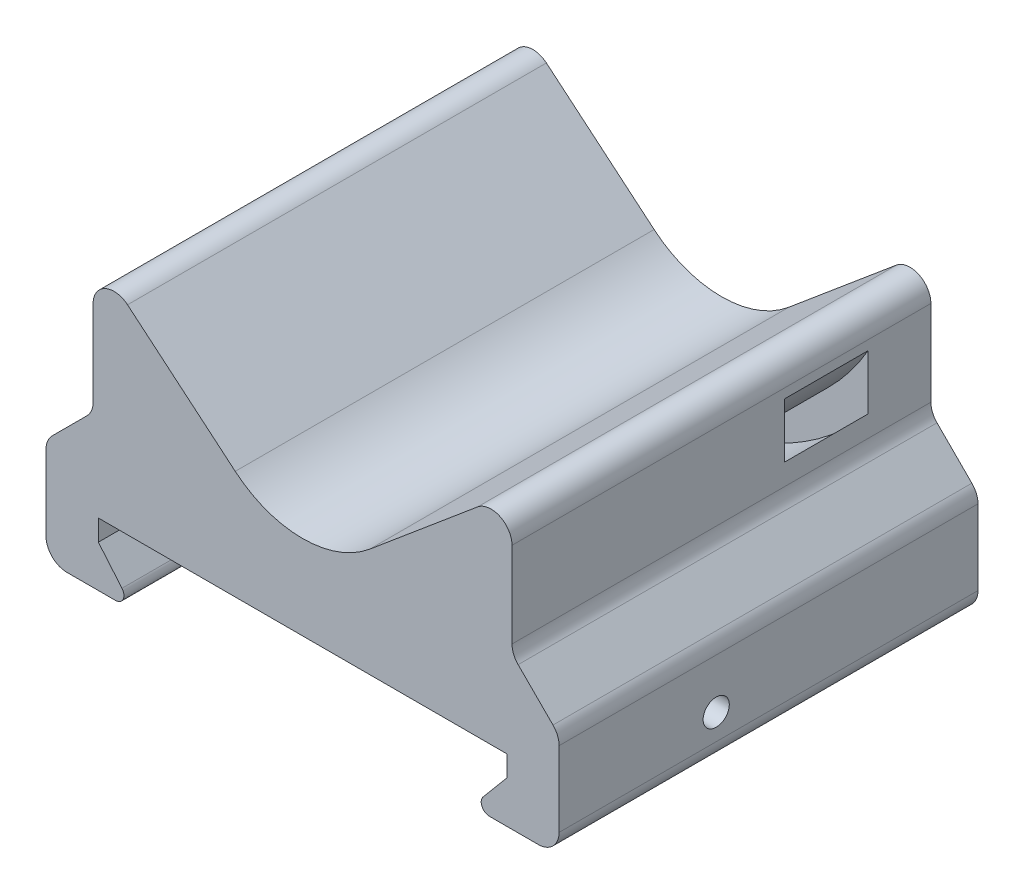
SolidWorks part; units mm, degrees
ref_plane "Front Plane" through (0, 0, 0) normal (0, 0, 1) x (1, 0, 0)
ref_plane "Top Plane" through (0, 0, 0) normal (0, 1, 0) x (1, 0, 0)
ref_plane "Right Plane" through (0, 0, 0) normal (1, 0, 0) x (0, 0, -1)
sketch "Sketch1" plane through (0, 0, 0) normal (0, 0, 1) x (1, 0, 0)
  line L0 (0, 15.6125) -> (0, -8.5333) construction
  line L1 (6.4279, 10.3936) -> (16.7144, 19.0251)
  line L2 (20, 17.493) -> (20, 9.3284)
  line L3 (20.5858, 7.9142) -> (23.9142, 4.5858)
  line L4 (24.5, 3.1716) -> (24.5, -4)
  line L5 (22.5, -6) -> (17.8592, -6)
  line L7 (19.5, 0) -> (-19.5, 0)
  line L9 (-22.5, -6) -> (-17.8592, -6)
  line L10 (-24.5, 3.1716) -> (-24.5, -4)
  line L11 (-20.5858, 7.9142) -> (-23.9142, 4.5858)
  line L12 (-20, 17.493) -> (-20, 9.3284)
  line L13 (-6.4279, 10.3936) -> (-16.7144, 19.0251)
  line L14 (-19.05, -0.1) -> (19.05, -0.1) construction
  line L15 (19.05, -0.1) -> (19.05, -2.1) construction
  line L16 (19.05, -2.1) -> (13.05, -8.1) construction
  line L17 (13.05, -8.1) -> (-13.05, -8.1) construction
  line L18 (-13.05, -8.1) -> (-19.05, -2.1) construction
  line L19 (-19.05, -0.1) -> (-19.05, -2.1) construction
  line L20 (17.2464, -4.6858) -> (19.5, -2)
  line L21 (19.5, -2) -> (19.5, 0)
  line L22 (-19.5, -2) -> (-19.5, 0)
  line L23 (-17.2464, -4.6858) -> (-19.5, -2)
  arc A0 (-6.4279, 10.3936) -> (6.4279, 10.3936) centre (0, 18.0541) ccw
  arc A1 (20, 9.3284) -> (20.5858, 7.9142) centre (22, 9.3284) ccw
  arc A2 (23.9142, 4.5858) -> (24.5, 3.1716) centre (22.5, 3.1716) cw
  arc A3 (24.5, -4) -> (22.5, -6) centre (22.5, -4) cw
  arc A4 (-22.5, -6) -> (-24.5, -4) centre (-22.5, -4) cw
  arc A5 (-24.5, 3.1716) -> (-23.9142, 4.5858) centre (-22.5, 3.1716) cw
  arc A6 (-20.5858, 7.9142) -> (-20, 9.3284) centre (-22, 9.3284) ccw
  arc A7 (16.7144, 19.0251) -> (20, 17.493) centre (18, 17.493) cw
  arc A8 (-20, 17.493) -> (-16.7144, 19.0251) centre (-18, 17.493) cw
  arc A9 (17.8592, -6) -> (17.2464, -4.6858) centre (17.8592, -5.2) cw
  arc A10 (-17.2464, -4.6858) -> (-17.8592, -6) centre (-17.8592, -5.2) cw
  point P11 (0, 0)
  point P19 (0, 5)
  point P22 (20, 8.5)
  point P25 (24.5, 4)
  point P28 (24.5, -6)
  point P31 (-24.5, -6)
  point P34 (-24.5, 4)
  point P37 (-20, 8.5)
  point P40 (20, 21.782)
  point P43 (-20, 21.782)
  point P51 (0, -8.1)
  point P52 (0, -0.1)
  point P56 (16.1436, -6)
  point P59 (-16.1436, -6)
  dimension "D10" = 10
  dimension "D11" = 2
  dimension "D18" = 0.8
  dimension "D1" = 19.5
  dimension "D2" = 5
  dimension "D3" = 20
  dimension "D4" = 135
  dimension "D5" = 50
  dimension "D6" = 6
  dimension "D7" = 4
  dimension "D8" = 50
  dimension "D9" = 5
  dimension "D12" = 38.1
  dimension "D13" = 135
  dimension "D14" = 8
  dimension "D15" = 2
  dimension "D16" = 0.2
  dimension "D17" = 2
extrude "Boss-Extrude1" add sketch "Sketch1" along normal blind 40
sketch "Sketch2" plane through (0, 0, 0) normal (1, 0, 0) x (0, 0, -1)
  line L0 (-40, 0) -> (0, 0) construction
  line L1 (-6, 5) -> (-14, 5)
  line L2 (-6, 5) -> (-6, 2)
  line L3 (-6, 2) -> (-14, 2)
  line L4 (-14, 5) -> (-14, 2)
  line L5 (0, 4.5858) -> (0, 7.9142) construction
  line L6 (-46, 5) -> (-54, 5)
  line L7 (-46, 5) -> (-46, 2)
  line L8 (-46, 2) -> (-54, 2)
  line L9 (-54, 5) -> (-54, 2)
  line L10 (-86, 5) -> (-94, 5)
  line L11 (-86, 5) -> (-86, 2)
  line L12 (-86, 2) -> (-94, 2)
  line L13 (-94, 5) -> (-94, 2)
  line L14 (-29.3538, 28.0541) -> (55.5998, 28.0541) construction
  line L15 (-40, 8.0541) -> (0, 8.0541) construction
  dimension "D1" = 8
  dimension "D2" = 3
  dimension "D3" = 2
  dimension "D4" = 6
  dimension "D6" = 20
  dimension "D5" = 3
revolve "Cut-Revolve1" cut sketch "Sketch2" angle 360 about L14
hole_wizard "M3x0.5 Tapped Hole1" positions "Sketch3" profile "Sketch4" tap size "M3x0.5" standard "ANSI Metric" end condition through all
sketch "Sketch3" plane through (-24.5, 0, 0) normal (-1, 0, 0) x (0, 0, 1)
  line L0 (75, -1.5555) -> (25, -1.5555) construction
  point P0 (25, -1.5555)
  point P2 (75, -1.5555)
  point P10 (50, -1.5555)
  dimension "D1" = 50
  dimension "D2" = 50
sketch "Sketch4" plane through (-24.5, -1.5555, 25) normal (0, 1, 0) x (0, 0, 1)
  line L0 (0, 0) -> (0, 49)
  line L1 (0, 49) -> (1.25, 49)
  line L2 (1.25, 49) -> (1.25, 0.275)
  line L3 (1.25, 0.275) -> (1.525, 0)
  line L5 (1.525, 0) -> (0, 0)
  line L6 (-1.25, 0.275) -> (-1.525, 0) construction
  line L11 (0, -6.35) -> (0, 107.95) construction
  dimension "Thru Tap Drill Dia." = 2.5
  dimension "Thru Tap Drill Depth" = 49
  dimension "Near C'Sink Dia." = 3.05
  dimension "Near C'Sink Angle" = 90
cosmetic thread "Hole Thread2" parameters "D2"=3
